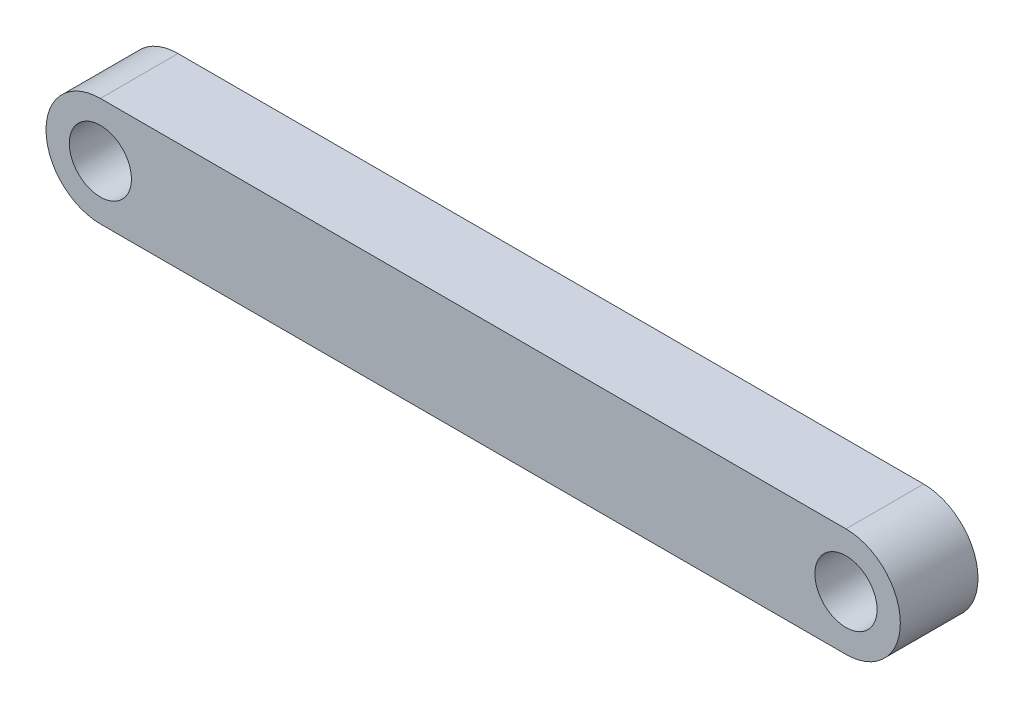
SolidWorks part; units mm, degrees
ref_plane "Front Plane" through (0, 0, 0) normal (0, 0, 1) x (1, 0, 0)
ref_plane "Top Plane" through (0, 0, 0) normal (0, 1, 0) x (1, 0, 0)
ref_plane "Right Plane" through (0, 0, 0) normal (1, 0, 0) x (0, 0, -1)
sketch "Sketch1" plane through (0, 0, 0) normal (0, 0, 1) x (1, 0, 0)
  line L0 (609.6, 0) -> (0, 0) construction
  line L1 (609.6, -44.45) -> (0, -44.45)
  line L2 (609.6, 44.45) -> (0, 44.45)
  arc A0 (609.6, -44.45) -> (609.6, 44.45) centre (609.6, 0) ccw
  arc A1 (0, 44.45) -> (0, -44.45) centre (0, 0) ccw
  circle A2 centre (609.6, 0) radius 25.4
  circle A3 centre (0, 0) radius 25.4
  point P3 (304.8, 0)
  dimension "D1" = 50.8
  dimension "D2" = 44.45
  dimension "D3" = 609.6
extrude "Boss-Extrude1" add sketch "Sketch1" along normal mid plane 63.5
